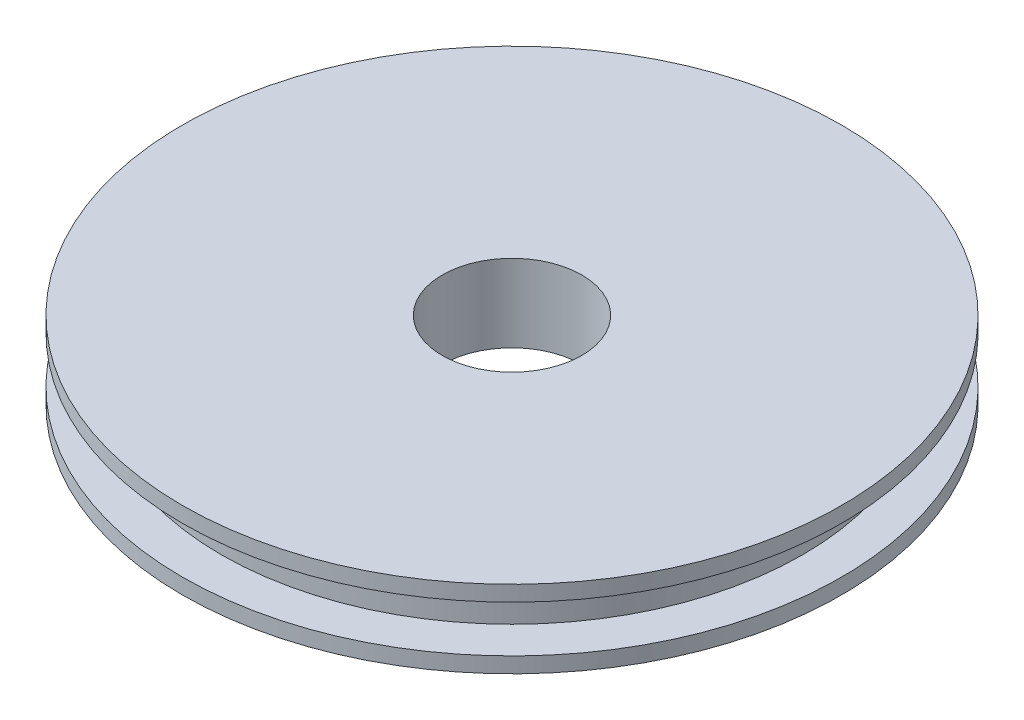
SolidWorks part; units mm, degrees
ref_plane "Front Plane" through (0, 0, 0) normal (0, 0, 1) x (1, 0, 0)
ref_plane "Top Plane" through (0, 0, 0) normal (0, 1, 0) x (1, 0, 0)
ref_plane "Right Plane" through (0, 0, 0) normal (1, 0, 0) x (0, 0, -1)
sketch "Sketch1" plane through (0, 0, 0) normal (0, 0, 1) x (1, 0, 0)
  line L0 (0, 0) -> (0, 32.9498) construction
  line L1 (9, 10) -> (42.5, 10)
  line L2 (42.5, 10) -> (42.5, 8)
  line L3 (42.5, 0) -> (42.5, 2)
  line L4 (42.5, 0) -> (9, 0)
  line L5 (9, 10) -> (9, 0)
  line L6 (42.5, 8) -> (37.5, 8)
  line L7 (37.5, 8) -> (37.5, 2)
  line L8 (37.5, 2) -> (42.5, 2)
  dimension "D1" = 10
  dimension "D2" = 6
  dimension "D3" = 18
  dimension "D4" = 75
  dimension "D5" = 85
revolve "Revolve1" add sketch "Sketch1" angle 360 about L0
sketch "Sketch2" plane through (0, 0, 0) normal (0, -1, 0) x (1, 0, 0)
  point P0 (0, 0)
